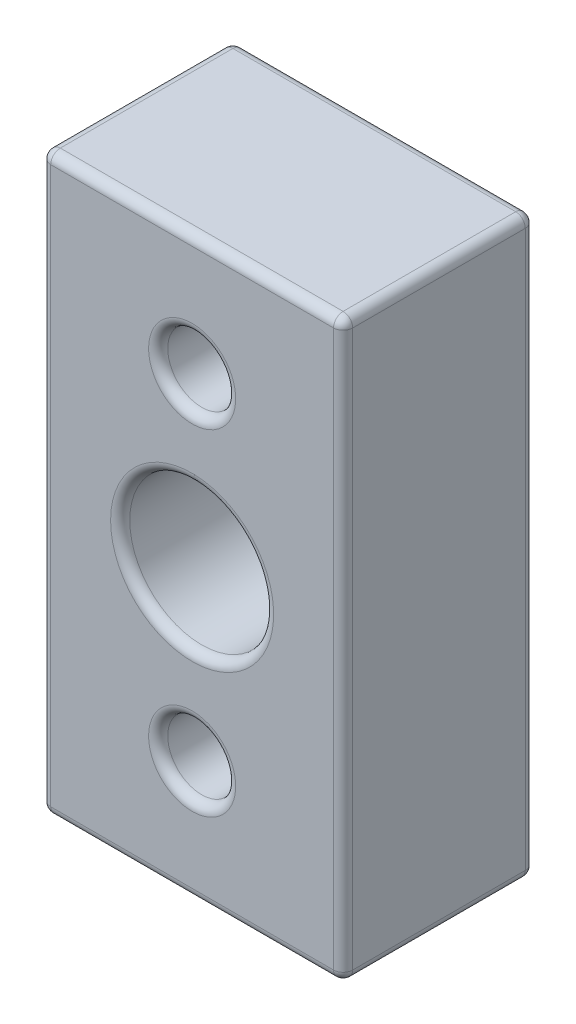
SolidWorks part; units mm, degrees
ref_plane "Front Plane" through (0, 0, 0) normal (1, 0, 0) x (0, 1, 0)
ref_plane "Top Plane" through (0, 0, 0) normal (0, 0, 1) x (0, 1, 0)
ref_plane "Right Plane" through (0, 0, 0) normal (0, 1, 0) x (-1, 0, 0)
sketch "Sketch1" plane through (0, 0, 0) normal (0, 0, 1) x (0, 1, 0)
  line L1 (-38.1, -20.0025) -> (38.1, -20.0025)
  line L2 (-38.1, -20.0025) -> (-38.1, 20.0025)
  line L3 (-38.1, 20.0025) -> (38.1, 20.0025)
  line L4 (38.1, -20.0025) -> (38.1, 20.0025)
  line L5 (-38.1, -20.0025) -> (38.1, 20.0025) construction
  line L6 (-38.1, 20.0025) -> (38.1, -20.0025) construction
  point P0 (0, 0)
  dimension "D1" = 40.005
  dimension "D2" = 76.2
extrude "Boss-Extrude1" add sketch "Sketch1" along normal blind 25.4
sketch "Sketch2" plane through (0, 0, 25.4) normal (0, 0, 1) x (1, 0, 0)
  circle A0 centre (0, 0) radius 9.5301
  dimension "D1" = 19.0602
extrude "Cut-Extrude1" cut sketch "Sketch2" against normal through all
sketch "Sketch3" plane through (0, 0, 25.4) normal (0, 0, 1) x (1, 0, 0)
  line L0 (0, 38.1) -> (0, -38.1) construction
  line L1 (20.0025, 38.1) -> (-20.0025, 38.1) construction
  line L2 (-20.0025, -38.1) -> (20.0025, -38.1) construction
  circle A0 centre (0, 22.225) radius 4.4996
  circle A1 centre (0, -22.225) radius 4.4996
  dimension "D1" = 8.9992
  dimension "D2" = 15.875
  dimension "D3" = 60.325
extrude "Cut-Extrude2" cut sketch "Sketch3" against normal through all
fillet "Fillet1" radius 1.27 18 edges at (20.0025, -38.1, 12.7) (20.0025, 38.1, 12.7) (-20.0025, 38.1, 12.7) (-20.0025, -38.1, 12.7) (20.0025, 0, 25.4) (0, -38.1, 25.4) (-20.0025, 0, 25.4) (0, 38.1, 25.4) (9.5301, 0, 25.4) (4.4996, -22.225, 25.4) (4.4996, 22.225, 25.4) (-20.0025, 0, 0) (0, -38.1, 0) (20.0025, 0, 0) (0, 38.1, 0) (9.5301, 0, 0) (4.4996, -22.225, 0) (4.4996, 22.225, 0)
equation "\"ScrewDia\"= 0.75"
equation "\"BoreTol\"= 0.0008"
equation "\"BoreDia\"= \"ScrewDia\" + \"BoreTol\" / 2"
equation "\"BearingLen\"= 1.0"
equation "\"BeamWidth\"= 1.575"
equation "\"Width\"= \"BeamWidth\""
equation "\"BoltSpacing\"= 1.75"
equation "\"BoltHoleDia\"= 0.3543"
equation "\"EdgeDist\"= 0.625"
equation "\"Length\"= \"BoltSpacing\" + 2 * \"EdgeDist\""
equation "\"BoreX\"= \"Length\" / 2"
equation "\"BoreY\"= \"Width\" / 2"
equation "\"BoltX1\"= \"BoreX\" - \"BoltSpacing\" / 2"
equation "\"BoltX2\"= \"BoreX\" + \"BoltSpacing\" / 2"
equation "\"EdgeRatio\"= \"EdgeDist\" / \"BoltHoleDia\""
equation "\"D2@Sketch1\"=\"Length\""
equation "\"D1@Sketch1\"=\"Width\""
equation "\"D1@Boss-Extrude1\"=\"BearingLen\""
equation "\"D1@Sketch2\"=\"BoreDia\""
equation "\"D1@Sketch3\"=\"BoltHoleDia\""
equation "\"D2@Sketch3\"=\"BoltX1\""
equation "\"D3@Sketch3\"=\"BoltX2\""
